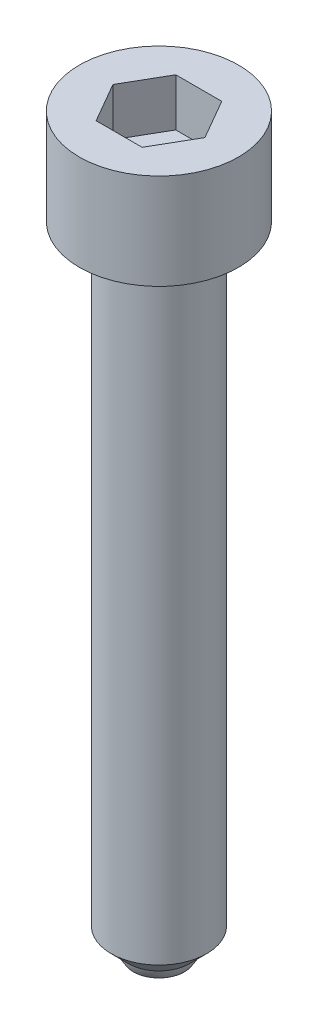
SolidWorks part; units mm, degrees
material "AISI 304"
ref_plane "Front Plane" through (0, 0, 0) normal (0, 0, 1) x (1, 0, 0)
ref_plane "Top Plane" through (0, 0, 0) normal (0, 1, 0) x (1, 0, 0)
ref_plane "Right Plane" through (0, 0, 0) normal (1, 0, 0) x (0, 0, -1)
sketch "Sketch1" plane through (0, 0, 0) normal (0, 0, 1) x (1, 0, 0)
  line L0 (0, 61.6916) -> (0, -59.3578) construction
  line L1 (0, -40) -> (1.6, -40)
  line L2 (3, -38.3079) -> (3, 0)
  line L3 (3, 0) -> (5, 0)
  line L4 (5, 0) -> (5, 6)
  line L5 (5, 6) -> (0, 6)
  line L6 (0, 6) -> (0, -40)
  line L7 (1.9079, -39.4) -> (3, -38.3079)
  arc A0 (1.6, -40) -> (1.9079, -39.4) centre (0, -38.8) ccw
  dimension "D6" = 3.2
  dimension "D8" = 2
  dimension "D1" = 40
  dimension "D2" = 10
  dimension "D3" = 6
  dimension "D4" = 6
  dimension "D5" = 45
  dimension "D7" = 0.6
revolve "Revolve1" add sketch "Sketch1" angle 360 about L0
sketch "Sketch2" plane through (0, 6, 0) normal (0, 1, 0) x (-1, 0, 0)
  line L1 (-1.4434, -2.5) -> (1.4434, -2.5)
  line L2 (1.4434, -2.5) -> (2.8868, 0)
  line L3 (2.8868, 0) -> (1.4434, 2.5)
  line L4 (1.4434, 2.5) -> (-1.4434, 2.5)
  line L5 (-1.4434, 2.5) -> (-2.8868, 0)
  line L6 (-2.8868, 0) -> (-1.4434, -2.5)
  circle A0 centre (0, 0) radius 2.5 construction
  dimension "D1" = 5
extrude "Cut-Extrude1" cut sketch "Sketch2" against normal blind 3
